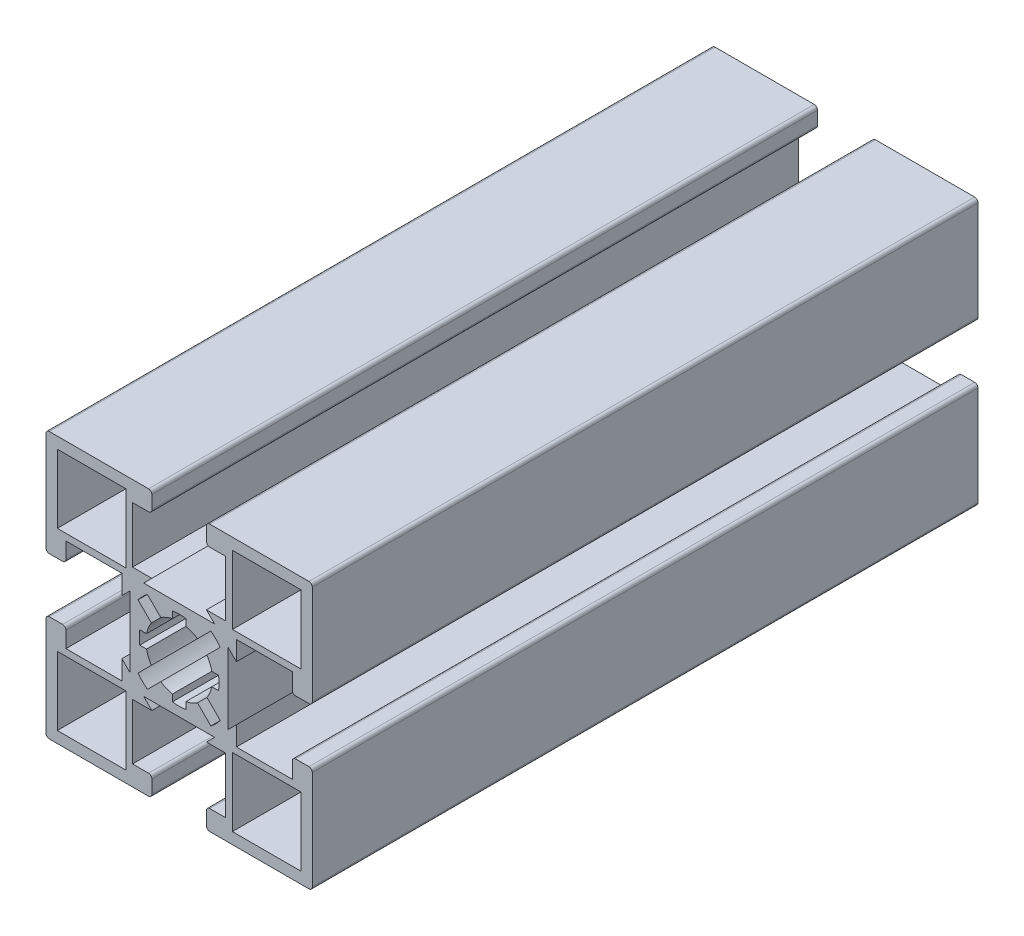
SolidWorks part; units mm, degrees
ref_plane "前视基准面" through (0, 0, 0) normal (0, 0, 1) x (1, 0, 0)
ref_plane "上视基准面" through (0, 0, 0) normal (0, 1, 0) x (1, 0, 0)
ref_plane "右视基准面" through (0, 0, 0) normal (1, 0, 0) x (0, 0, -1)
sketch "草图1" plane through (0, 0, 0) normal (0, 0, 1) x (1, 0, 0)
  line L0 (-7.2716, 19.057) -> (-17.5716, 19.057)
  line L1 (-17.5716, 19.057) -> (-17.5716, 8.757)
  line L2 (-3.3716, 9.357) -> (-6.2716, 9.357)
  line L3 (-16.2716, 7.757) -> (-16.2716, 5.357)
  line L4 (-16.7716, 4.857) -> (-18.7716, 4.857)
  line L5 (-19.2716, 5.357) -> (-19.2716, 20.257)
  line L6 (-18.7716, 20.757) -> (-3.8716, 20.757)
  line L7 (-3.3716, 20.257) -> (-3.3716, 18.257)
  line L8 (-3.8716, 17.757) -> (-6.2716, 17.757)
  line L9 (-7.8716, 7.757) -> (-7.8716, 4.857)
  line L10 (-16.2716, 7.757) -> (-7.8716, 7.757)
  line L11 (-17.5716, 8.757) -> (-7.2716, 8.757)
  line L12 (-6.2716, 17.757) -> (-6.2716, 9.357)
  line L13 (-7.2716, 19.057) -> (-7.2716, 8.757)
  line L14 (-7.8716, 4.857) -> (-6.6416, 6.087)
  line L15 (-4.6016, 8.127) -> (-3.3716, 9.357)
  line L16 (8.7284, 19.057) -> (19.0284, 19.057)
  line L17 (19.0284, 19.057) -> (19.0284, 8.757)
  line L18 (4.8284, 9.357) -> (7.7284, 9.357)
  line L19 (17.7284, 7.757) -> (17.7284, 5.357)
  line L20 (18.2284, 4.857) -> (20.2284, 4.857)
  line L21 (20.7284, 5.357) -> (20.7284, 20.257)
  line L22 (20.2284, 20.757) -> (5.3284, 20.757)
  line L23 (4.8284, 20.257) -> (4.8284, 18.257)
  line L24 (5.3284, 17.757) -> (7.7284, 17.757)
  line L25 (9.3284, 7.757) -> (9.3284, 4.857)
  line L26 (17.7284, 7.757) -> (9.3284, 7.757)
  line L27 (19.0284, 8.757) -> (8.7284, 8.757)
  line L28 (7.7284, 17.757) -> (7.7284, 9.357)
  line L29 (8.7284, 19.057) -> (8.7284, 8.757)
  line L30 (9.3284, 4.857) -> (8.0984, 6.087)
  line L31 (6.0584, 8.127) -> (4.8284, 9.357)
  line L32 (-7.2716, -17.543) -> (-17.5716, -17.543)
  line L33 (-17.5716, -17.543) -> (-17.5716, -7.243)
  line L34 (-3.3716, -7.843) -> (-6.2716, -7.843)
  line L35 (-16.2716, -6.243) -> (-16.2716, -3.843)
  line L36 (-16.7716, -3.343) -> (-18.7716, -3.343)
  line L37 (-19.2716, -3.843) -> (-19.2716, -18.743)
  line L38 (-18.7716, -19.243) -> (-3.8716, -19.243)
  line L39 (-3.3716, -18.743) -> (-3.3716, -16.743)
  line L40 (-3.8716, -16.243) -> (-6.2716, -16.243)
  line L41 (-7.8716, -6.243) -> (-7.8716, -3.343)
  line L42 (-16.2716, -6.243) -> (-7.8716, -6.243)
  line L43 (-17.5716, -7.243) -> (-7.2716, -7.243)
  line L44 (-6.2716, -16.243) -> (-6.2716, -7.843)
  line L45 (-7.2716, -17.543) -> (-7.2716, -7.243)
  line L46 (-7.8716, -3.343) -> (-6.6416, -4.573)
  line L47 (-4.6016, -6.613) -> (-3.3716, -7.843)
  line L48 (8.7284, -17.543) -> (19.0284, -17.543)
  line L49 (19.0284, -17.543) -> (19.0284, -7.243)
  line L50 (4.8284, -7.843) -> (7.7284, -7.843)
  line L51 (17.7284, -6.243) -> (17.7284, -3.843)
  line L52 (18.2284, -3.343) -> (20.2284, -3.343)
  line L53 (20.7284, -3.843) -> (20.7284, -18.743)
  line L54 (20.2284, -19.243) -> (5.3284, -19.243)
  line L55 (4.8284, -18.743) -> (4.8284, -16.743)
  line L56 (5.3284, -16.243) -> (7.7284, -16.243)
  line L57 (9.3284, -6.243) -> (9.3284, -3.343)
  line L58 (17.7284, -6.243) -> (9.3284, -6.243)
  line L59 (19.0284, -7.243) -> (8.7284, -7.243)
  line L60 (7.7284, -16.243) -> (7.7284, -7.843)
  line L61 (8.7284, -17.543) -> (8.7284, -7.243)
  line L62 (9.3284, -3.343) -> (8.0984, -4.573)
  line L63 (6.0584, -6.613) -> (4.8284, -7.843)
  line L64 (-6.6416, 6.087) -> (-6.6416, -4.573)
  line L65 (-4.6016, -6.613) -> (6.0584, -6.613)
  line L66 (8.0984, -4.573) -> (8.0984, 6.087)
  line L67 (6.0584, 8.127) -> (-4.6016, 8.127)
  line L68 (-5.4486, 5.5198) -> (-3.4428, 3.514)
  line L69 (3.4854, -3.4142) -> (5.4912, -5.42)
  line L70 (-4.0344, 6.934) -> (-2.0286, 4.9282)
  line L71 (4.8996, -2) -> (6.9054, -4.0058)
  line L72 (-4.0344, -5.42) -> (-2.0286, -3.4142)
  line L73 (4.8996, 3.514) -> (6.9054, 5.5198)
  line L74 (-5.4486, -4.0058) -> (-3.4428, -2)
  line L75 (3.4854, 4.9282) -> (5.4912, 6.934)
  line L76 (-0.2716, 6.6731) -> (-0.2716, 5.656)
  line L77 (-0.2716, -4.142) -> (-0.2716, -5.1591)
  line L78 (1.7284, 6.6731) -> (1.7284, 5.656)
  line L79 (1.7284, -4.142) -> (1.7284, -5.1591)
  line L80 (-5.1877, -0.243) -> (-4.1706, -0.243)
  line L81 (5.6274, -0.243) -> (6.6445, -0.243)
  line L82 (-5.1877, 1.757) -> (-4.1706, 1.757)
  line L83 (5.6274, 1.757) -> (6.6445, 1.757)
  arc A0 (-16.7716, 4.857) -> (-16.2716, 5.357) centre (-16.7716, 5.357) ccw
  arc A1 (-19.2716, 5.357) -> (-18.7716, 4.857) centre (-18.7716, 5.357) ccw
  arc A2 (-18.7716, 20.757) -> (-19.2716, 20.257) centre (-18.7716, 20.257) ccw
  arc A3 (-3.3716, 20.257) -> (-3.8716, 20.757) centre (-3.8716, 20.257) ccw
  arc A4 (-3.8716, 17.757) -> (-3.3716, 18.257) centre (-3.8716, 18.257) ccw
  arc A5 (17.7284, 5.357) -> (18.2284, 4.857) centre (18.2284, 5.357) ccw
  arc A6 (20.2284, 4.857) -> (20.7284, 5.357) centre (20.2284, 5.357) ccw
  arc A7 (20.7284, 20.257) -> (20.2284, 20.757) centre (20.2284, 20.257) ccw
  arc A8 (5.3284, 20.757) -> (4.8284, 20.257) centre (5.3284, 20.257) ccw
  arc A9 (4.8284, 18.257) -> (5.3284, 17.757) centre (5.3284, 18.257) ccw
  arc A10 (-16.2716, -3.843) -> (-16.7716, -3.343) centre (-16.7716, -3.843) ccw
  arc A11 (-18.7716, -3.343) -> (-19.2716, -3.843) centre (-18.7716, -3.843) ccw
  arc A12 (-19.2716, -18.743) -> (-18.7716, -19.243) centre (-18.7716, -18.743) ccw
  arc A13 (-3.8716, -19.243) -> (-3.3716, -18.743) centre (-3.8716, -18.743) ccw
  arc A14 (-3.3716, -16.743) -> (-3.8716, -16.243) centre (-3.8716, -16.743) ccw
  arc A15 (18.2284, -3.343) -> (17.7284, -3.843) centre (18.2284, -3.843) ccw
  arc A16 (20.7284, -3.843) -> (20.2284, -3.343) centre (20.2284, -3.843) ccw
  arc A17 (20.2284, -19.243) -> (20.7284, -18.743) centre (20.2284, -18.743) ccw
  arc A18 (4.8284, -18.743) -> (5.3284, -19.243) centre (5.3284, -18.743) ccw
  arc A19 (5.3284, -16.243) -> (4.8284, -16.743) centre (5.3284, -16.743) ccw
  arc A20 (3.4854, 4.9282) -> (1.7284, 5.656) centre (0.7284, 0.757) ccw
  arc A21 (-0.2716, 5.656) -> (-2.0286, 4.9282) centre (0.7284, 0.757) ccw
  arc A22 (-3.4428, 3.514) -> (-4.1706, 1.757) centre (0.7284, 0.757) ccw
  arc A23 (-4.1706, -0.243) -> (-3.4428, -2) centre (0.7284, 0.757) ccw
  arc A24 (-2.0286, -3.4142) -> (-0.2716, -4.142) centre (0.7284, 0.757) ccw
  arc A25 (1.7284, -4.142) -> (3.4854, -3.4142) centre (0.7284, 0.757) ccw
  arc A26 (4.8996, -2) -> (5.6274, -0.243) centre (0.7284, 0.757) ccw
  arc A27 (5.6274, 1.757) -> (4.8996, 3.514) centre (0.7284, 0.757) ccw
  arc A28 (5.4912, -5.42) -> (6.9054, -4.0058) centre (0.7284, 0.757) ccw
  arc A29 (6.9054, 5.5198) -> (5.4912, 6.934) centre (0.7284, 0.757) ccw
  arc A30 (-4.0344, 6.934) -> (-5.4486, 5.5198) centre (0.7284, 0.757) ccw
  arc A31 (-5.4486, -4.0058) -> (-4.0344, -5.42) centre (0.7284, 0.757) ccw
  arc A32 (-0.2716, -5.1591) -> (1.7284, -5.1591) centre (0.7284, 0.757) ccw
  arc A33 (6.6445, -0.243) -> (6.6445, 1.757) centre (0.7284, 0.757) ccw
  arc A34 (1.7284, 6.6731) -> (-0.2716, 6.6731) centre (0.7284, 0.757) ccw
  arc A35 (-5.1877, 1.757) -> (-5.1877, -0.243) centre (0.7284, 0.757) ccw
extrude "凸台-拉伸1" add sketch "草图1" along normal blind 100
